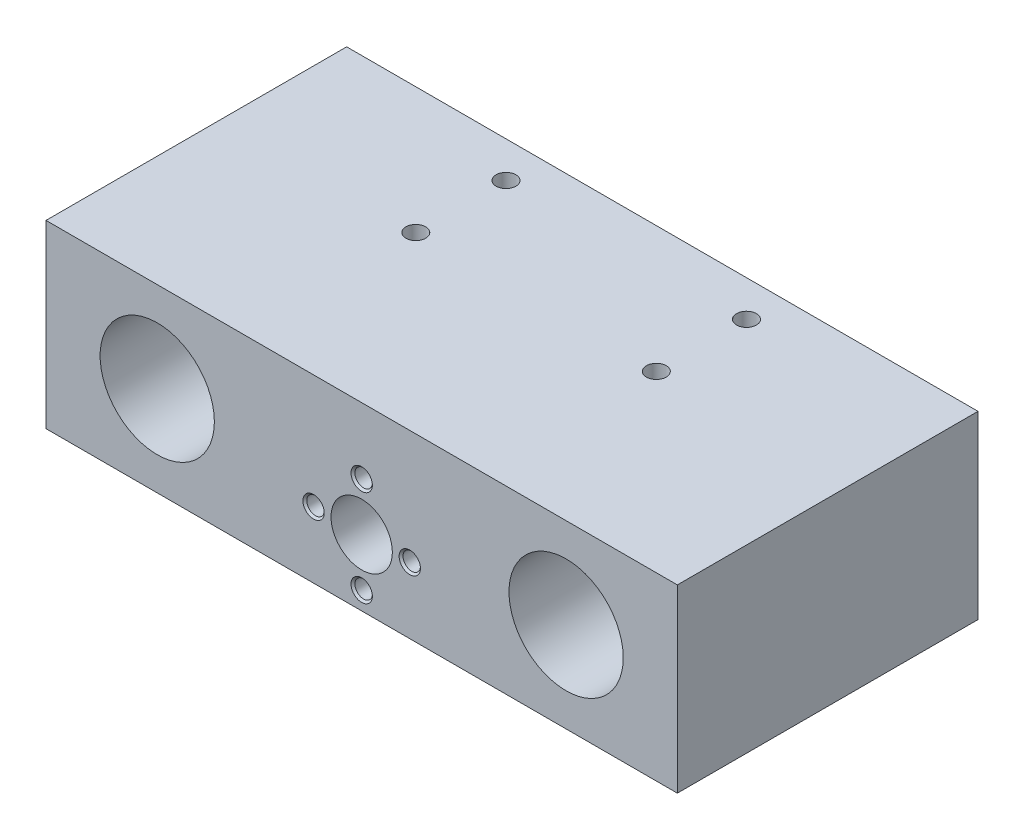
SolidWorks part; units mm, degrees
material "AISI 1020"
ref_plane "Plano frontal" through (0, 0, 0) normal (0, 0, 1) x (1, 0, 0)
ref_plane "Plano superior" through (0, 0, 0) normal (0, 1, 0) x (1, 0, 0)
ref_plane "Plano direito" through (0, 0, 0) normal (1, 0, 0) x (0, 0, -1)
sketch "Esboço1" plane through (0, 0, 0) normal (0, 0, 1) x (1, 0, 0)
  line L0 (0, 0) -> (0, 48.0252) construction
  line L2 (-52.5, -15) -> (52.5, -15)
  line L3 (-52.5, -15) -> (-52.5, 15)
  line L4 (-52.5, 15) -> (52.5, 15)
  line L5 (52.5, -15) -> (52.5, 15)
  line L6 (-52.5, -15) -> (52.5, 15) construction
  line L7 (-52.5, 15) -> (52.5, -15) construction
  circle A0 centre (-34, 0) radius 9.5
  circle A1 centre (34, 0) radius 9.5
  circle A3 centre (0, -4) radius 4.25
  dimension "D1" = 19
  dimension "D5" = 11
  dimension "D6" = 8.5
  dimension "D2" = 68
  dimension "D3" = 30
  dimension "D4" = 105
extrude "Ressalto-extrusão1" add sketch "Esboço1" along normal mid plane 50
sketch "Sketch1" plane through (0, 0, -25) normal (0, 0, 1) x (1, 0, 0)
  line L1 (52.5, 15) -> (-52.5, 15) construction
  line L3 (0, 0) -> (0, 15) construction
  line L11 (0, 11) -> (-12.5, 11)
  line L12 (-12.5, 11) -> (-12.5, 6.5)
  line L13 (-12.5, 6.5) -> (12.5, 6.5)
  line L15 (12.5, 11) -> (12.5, 6.5)
  line L16 (0, 11) -> (12.5, 11)
  point P12 (0, 6.5)
  dimension "D1" = 25
  dimension "D2" = 4
  dimension "D4" = 4.5
extrude "Cut-Extrude1" [suppressed] cut sketch "Sketch1" along normal blind 25
sketch "Sketch2" [suppressed] plane through (0, 18, 0) normal (0, 1, 0) x (1, 0, 0)
  line L1 (52.5, 25) -> (-52.5, 25) construction
  circle A0 centre (0, 12.5) radius 4
  dimension "D2" = 8
  dimension "D1" = 12.5
sketch "Sketch3" plane through (0, 15, 0) normal (0, 1, 0) x (1, 0, 0)
  line L0 (0, 0) -> (0, 25) construction
  line L1 (52.5, 25) -> (-52.5, 25) construction
  circle A0 centre (20, 4) radius 2
  circle A1 centre (20, 19) radius 2
  circle A2 centre (-20, 19) radius 2
  circle A3 centre (-20, 4) radius 2
  dimension "D1" = 4
  dimension "D2" = 15
  dimension "D3" = 40
  dimension "D4" = 6
hole_wizard "M4x0.7 Tapped Hole1" positions "Sketch4" profile "Sketch5" tap size "M4x0.7" standard "ANSI Metric"
sketch "Sketch4" plane through (0, 15, 0) normal (0, 1, 0) x (1, 0, 0)
  point P0 (20, 19)
  point P3 (20, 4)
  point P6 (-20, 4)
  point P9 (-20, 19)
sketch "Sketch5" plane through (20, 15, -19) normal (1, 0, 0) x (0, 0, 1)
  line L0 (0, 0) -> (0, 12.4914)
  line L1 (0, 12.4914) -> (1.65, 11.5)
  line L2 (1.65, 11.5) -> (1.65, 0)
  line L5 (1.65, 0) -> (0, 0)
  line L10 (0, 12.4914) -> (-1.65, 11.5) construction
  line L11 (0, -6.35) -> (0, 107.95) construction
  dimension "Tap Drill Dia." = 3.3
  dimension "Tap Drill Depth" = 11.5
  dimension "Drill Angle" = 118
cosmetic thread "Hole Thread1" parameters "D1"=8, "D2"=4
cosmetic thread "Hole Thread2" parameters "D1"=8, "D2"=4
cosmetic thread "Hole Thread3" parameters "D1"=8, "D2"=4
cosmetic thread "Hole Thread4" parameters "D1"=8, "D2"=4
sketch "Esboço4" plane through (0, 0, 25) normal (0, 0, 1) x (1, 0, 0)
  circle A1 centre (0, -4) radius 5.1
  circle A2 centre (0, -4) radius 4.25 construction
  dimension "D1" = 10.2
extrude "Corte-extrusão1" cut sketch "Esboço4" against normal blind 11
sketch "Esboço8" plane through (0, 0, 25) normal (0, 0, 1) x (1, 0, 0)
  circle A0 centre (0, -4) radius 8 construction
  circle A1 centre (0, -4) radius 4.25 construction
  circle A2 centre (0, -4) radius 8 construction
  circle A3 centre (0, -4) radius 8 construction
  circle A4 centre (0, -4) radius 8 construction
  point P5 (-8, -4)
  point P10 (0, 4)
  point P12 (8, -4)
  point P14 (0, -12)
  point P15 (0, -4)
  dimension "D1" = 16
hole_wizard "Furo roscado de M3.5x0.62" positions "Esboço9" profile "Esboço10" tap size "M3.5x0.6" standard "Ansi Metric"
sketch "Esboço9" plane through (0, 0, 25) normal (0, 0, 1) x (1, 0, 0)
  point P0 (-8, -4)
  point P3 (0, 4)
  point P6 (8, -4)
  point P9 (0, -12)
sketch "Esboço10" plane through (-8, -4, 25) normal (1, 0, 0) x (0, -1, 0)
  line L0 (0, 0) -> (0, 15.8712)
  line L1 (0, 15.8712) -> (1.45, 15)
  line L2 (1.45, 15) -> (1.45, 0.325)
  line L3 (1.45, 0.325) -> (1.775, 0)
  line L5 (1.775, 0) -> (0, 0)
  line L6 (-1.45, 0.325) -> (-1.775, 0) construction
  line L10 (0, 15.8712) -> (-1.45, 15) construction
  line L11 (0, -6.35) -> (0, 107.95) construction
  dimension "Tap Drill Dia." = 2.9
  dimension "Tap Drill Depth" = 15
  dimension "Near C'Sink Dia." = 3.55
  dimension "Near C'Sink Angle" = 90
  dimension "Drill Angle" = 118
cosmetic thread "Rosca de furo14" parameters "D1"=12, "D2"=3.5
cosmetic thread "Rosca de furo15" parameters "D1"=12, "D2"=3.5
cosmetic thread "Rosca de furo16" parameters "D1"=12, "D2"=3.5
cosmetic thread "Rosca de furo17" parameters "D1"=12, "D2"=3.5
